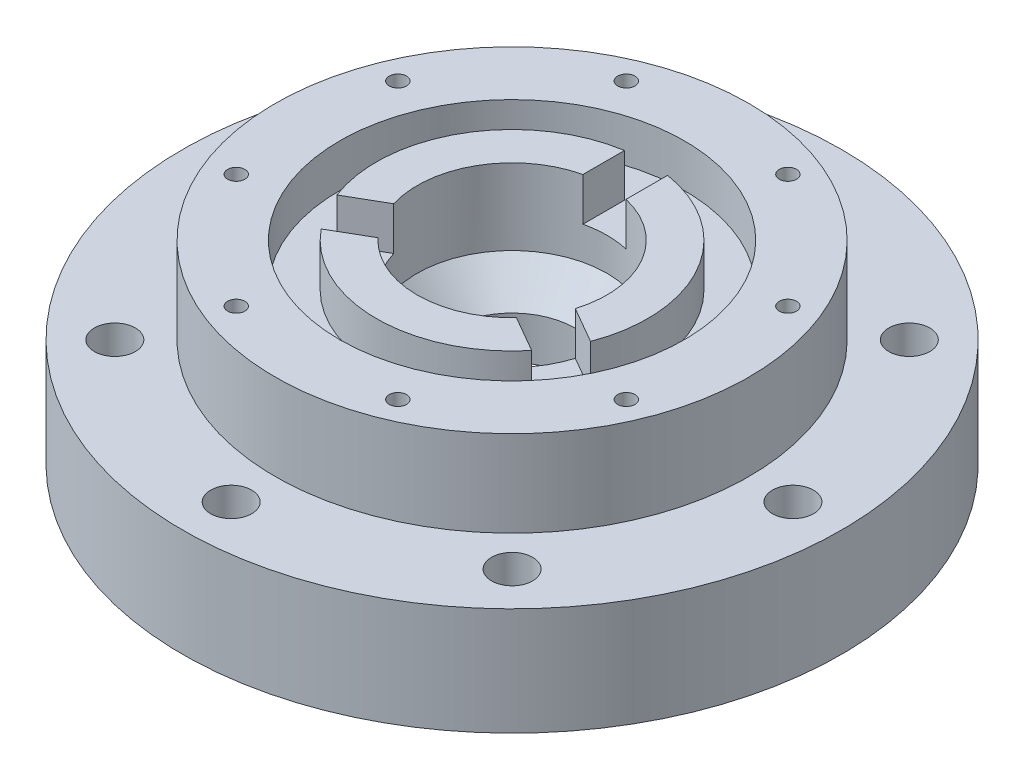
SolidWorks part; units mm, degrees
ref_plane "Front Plane" through (0, 0, 0) normal (0, 0, 1) x (1, 0, 0)
ref_plane "Top Plane" through (0, 0, 0) normal (0, 1, 0) x (1, 0, 0)
ref_plane "Right Plane" through (0, 0, 0) normal (1, 0, 0) x (0, 0, -1)
sketch "Sketch3" plane through (0, 0, 0) normal (1, 0, 0) x (0, 0, -1)
  line L2 (76.5, 15) -> (55, 15)
  line L3 (55, 15) -> (55, 35)
  line L4 (55, 35) -> (22.025, 35)
  line L7 (14.665, 0) -> (19.665, 0)
  line L8 (76.5, 15) -> (76.5, -10)
  line L9 (53.85, -10) -> (53.85, 86.2223) construction
  line L10 (76.5, -10) -> (53.85, -10)
  line L11 (14.665, 0) -> (14.665, 10)
  line L12 (14.665, 10) -> (22.025, 17.36)
  line L13 (22.025, 17.36) -> (22.025, 35)
  line L14 (0, 0) -> (0, 51.2471) construction
  line L15 (14.665, 10) -> (22.7366, 10) construction
  line L16 (65.2, -29.1535) -> (65.2, 61.9555) construction
  line L17 (0, 0) -> (14.665, 0) construction
  arc A3 (53.85, -10) -> (19.665, 0) centre (34.8984, -11.3553) ccw
  dimension "D8" = 19
  dimension "D1" = 10
  dimension "D2" = 55
  dimension "D3" = 76.5
  dimension "D4" = 45
  dimension "D6" = 53.85
  dimension "D7" = 14.665
  dimension "D9" = 25
  dimension "D11" = 10
  dimension "D12" = 45
  dimension "D13" = 44.05
  dimension "D14" = 5
  dimension "D15" = 65.2
revolve "Revolve1" add sketch "Sketch3" angle 360 about L14
sketch "Sketch4" plane through (0, 0, 0) normal (0, 1, 0) x (1, 0, 0)
  line L0 (0, 0) -> (-65.2, 0) construction
  circle A0 centre (-65.2, 0) radius 4.7625
  dimension "D2" = 9.525
  dimension "D1" = 65.2
extrude "Cut-Extrude2" cut sketch "Sketch4" along normal through all both and the other way through all contours A0
pattern_circular "CirPattern1" count 8 over 360 about axis through (0, 0, 0) along (0, 1, 0) of "Cut-Extrude2"
sketch "Sketch6" plane through (0, 35, 0) normal (0, 1, 0) x (1, 0, 0)
  circle A0 centre (0, 0) radius 31.5
  circle A1 centre (0, 0) radius 40
  point P19 (0, 0)
  dimension "D1" = 63
  dimension "D2" = 80
extrude "Cut-Extrude3" cut sketch "Sketch6" against normal blind 10
sketch "Sketch7" plane through (0, 35, 0) normal (0, 1, 0) x (1, 0, 0)
  line L0 (0, 0) -> (0, 31.5) construction
  line L1 (-5, 31.5) -> (5, 31.5)
  line L2 (5, 31.5) -> (5, 21.45)
  line L3 (5, 21.45) -> (-5, 21.45)
  line L4 (-5, 21.45) -> (-5, 31.5)
  circle A0 centre (0, 0) radius 31.5 construction
  circle A1 centre (0, 0) radius 22.025 construction
  point P8 (0, 31.5)
  dimension "D1" = 10
extrude "Cut-Extrude4" cut sketch "Sketch7" against normal blind 10
pattern_circular "CirPattern2" count 3 over 360 about axis through (0, 0, 0) along (0, 1, 0) of "Cut-Extrude4"
sketch "Sketch9" plane through (0, 35, 0) normal (0, 1, 0) x (1, 0, 0)
  line L0 (0, 0) -> (45.2701, 18.7515) construction
  line L1 (0, 0) -> (100.5921, 0) construction
  circle A0 centre (45.2701, 18.7515) radius 2
  point P6 (45.868, 17.2374)
  point P7 (100.5921, 0)
  dimension "D2" = 4
  dimension "D1" = 49
  dimension "D3" = 22.5
extrude "Cut-Extrude5" cut sketch "Sketch9" against normal blind 10
pattern_circular "CirPattern3" count 8 over 360 about axis through (0, 0, 0) along (0, 1, 0) of "Cut-Extrude5"
